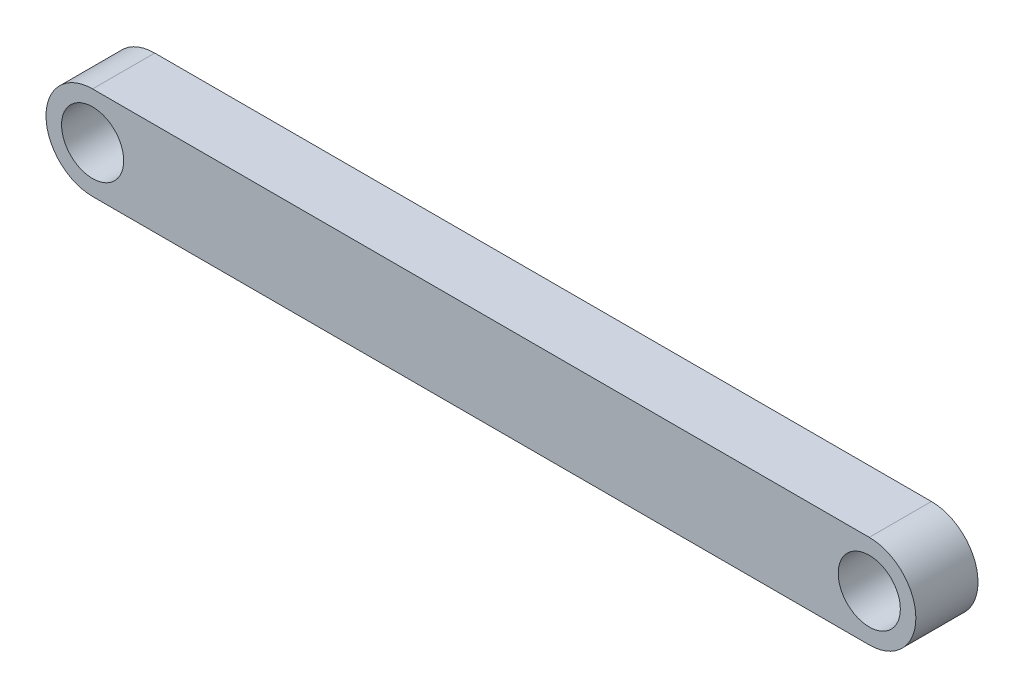
SolidWorks part; units mm, degrees
ref_plane "Спереди" through (0, 0, 0) normal (0, 0, 1) x (1, 0, 0)
ref_plane "Сверху" through (0, 0, 0) normal (0, 1, 0) x (1, 0, 0)
ref_plane "Справа" through (0, 0, 0) normal (1, 0, 0) x (0, 0, -1)
sketch "Эскиз1" plane through (0, 0, 0) normal (0, 0, 1) x (1, 0, 0)
  line L0 (-75, 0) -> (-325, 0) construction
  line L1 (-75, -15) -> (-325, -15)
  line L2 (-75, 15) -> (-325, 15)
  circle A0 centre (-75, 0) radius 10 construction
  circle A1 centre (-75, 0) radius 10
  arc A2 (-75, -15) -> (-75, 15) centre (-75, 0) ccw
  arc A3 (-325, 15) -> (-325, -15) centre (-325, 0) ccw
  circle A4 centre (-325, 0) radius 10
  arc A5 (-89.4876, -3.8869) -> (-60.5124, 3.8869) centre (-75, 0) ccw construction
  point P4 (-200, 0)
  dimension "D1" = 250
extrude "Бобышка-Вытянуть1" add sketch "Эскиз1" along normal blind 20
